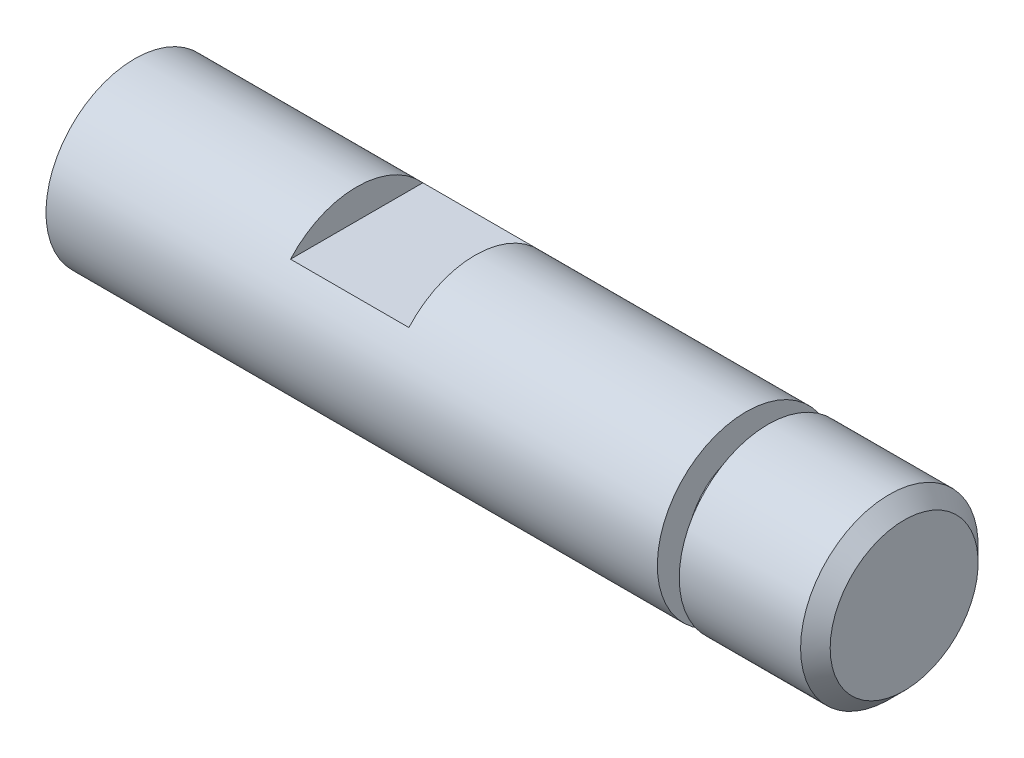
SolidWorks part; units mm, degrees
ref_plane "Plan de face" through (0, 0, 0) normal (0, 0, 1) x (1, 0, 0)
ref_plane "Plan de dessus" through (0, 0, 0) normal (0, 1, 0) x (1, 0, 0)
ref_plane "Plan de droite" through (0, 0, 0) normal (1, 0, 0) x (0, 0, -1)
sketch "Esquisse1" plane through (0, 0, 0) normal (0, 0, 1) x (1, 0, 0)
  line L0 (0, 0) -> (12.8037, 0) construction
  line L1 (0, 0) -> (0, 15.5366) construction
  line L2 (-26, 0) -> (26, 0)
  line L4 (-26, 0) -> (-26, 3)
  line L5 (-26, 3) -> (26, 3)
  line L6 (26, 0) -> (26, 3)
  point P4 (0, 0)
  dimension "D1" = 52
  dimension "D2" = 3
  dimension "D3" = 26
revolve "Révolution1" add sketch "Esquisse1" angle 360 about L0
chamfer "Chanfrein1" distance 0.5 angle 45 1 edges at (26, 0, 3)
sketch "Esquisse2" plane through (0, 0, 0) normal (0, 0, 1) x (1, 0, 0)
  line L0 (25.5, 3) -> (-26, 3) construction
  line L1 (25.5, 3) -> (-26, 3)
  line L3 (7.5, 4) -> (11.5, 4)
  line L4 (7.5, 4) -> (7.5, 2)
  line L5 (7.5, 2) -> (11.5, 2)
  line L6 (11.5, 4) -> (11.5, 2)
  line L7 (7.5, 4) -> (11.5, 2) construction
  line L8 (7.5, 2) -> (11.5, 4) construction
  point P2 (9.5, 3)
  dimension "D1" = 1
  dimension "D2" = 9.5
  dimension "D3" = 4
extrude "Enlèv. mat.-Extru.1" cut sketch "Esquisse2" against normal through all both and the other way through all contours L5 L6 L3 L4
sketch "Esquisse3" plane through (0, 0, 0) normal (0, 0, 1) x (1, 0, 0)
  line L2 (7.5, 3) -> (-26, 3) construction
  line L3 (-21.4, 3) -> (-20.66, 3)
  line L4 (0, 0) -> (0, 10.3249) construction
  line L5 (-21.4, 3) -> (-21.4, 2)
  line L6 (-21.4, 2) -> (-20.66, 2)
  line L7 (-20.66, 3) -> (-20.66, 2)
  line L8 (20.66, 3) -> (20.66, 2)
  line L9 (21.4, 2) -> (20.66, 2)
  line L10 (21.4, 3) -> (21.4, 2)
  line L11 (21.4, 3) -> (20.66, 3)
  line L17 (0, 0) -> (-35.8372, 0) construction
  dimension "D1" = 0.74
  dimension "D2" = 2
  dimension "D3" = 42.8
revolve "Enlèvement de matière-Révolution1" cut sketch "Esquisse3" angle 360 about L17
sketch "Esquisse4" plane through (-26, 0, 0) normal (-1, 0, 0) x (0, 0, 1)
  circle A1 centre (0, 0) radius 3
  circle A2 centre (0, 0) radius 3
  dimension "D1" = 0
extrude "Boss.-Extru.1" add sketch "Esquisse4" along normal blind 15
sketch "Esquisse5" plane through (0, 0, 0) normal (0, 0, 1) x (1, 0, 0)
  line L0 (11.5, 2) -> (7.5, 2) construction
  line L1 (-41, 3) -> (-29, 3)
  line L2 (-41, 3) -> (-41, 2)
  line L3 (-41, 2) -> (-29, 2)
  line L4 (-29, 3) -> (-29, 2)
  dimension "D1" = 12
extrude "Enlèv. mat.-Extru.2" cut sketch "Esquisse5" against normal through all both and the other way through all
sketch "Esquisse6" plane through (0, 0, 0) normal (0, 0, 1) x (1, 0, 0)
  line L1 (-50.2113, 11.2061) -> (0, 11.2061)
  line L2 (-50.2113, 11.2061) -> (-50.2113, -9.0114)
  line L3 (-50.2113, -9.0114) -> (0, -9.0114)
  line L4 (0, 11.2061) -> (0, -9.0114)
  dimension "D1" = 0
extrude "Enlèv. mat.-Extru.3" cut sketch "Esquisse6" against normal through all both and the other way through all
